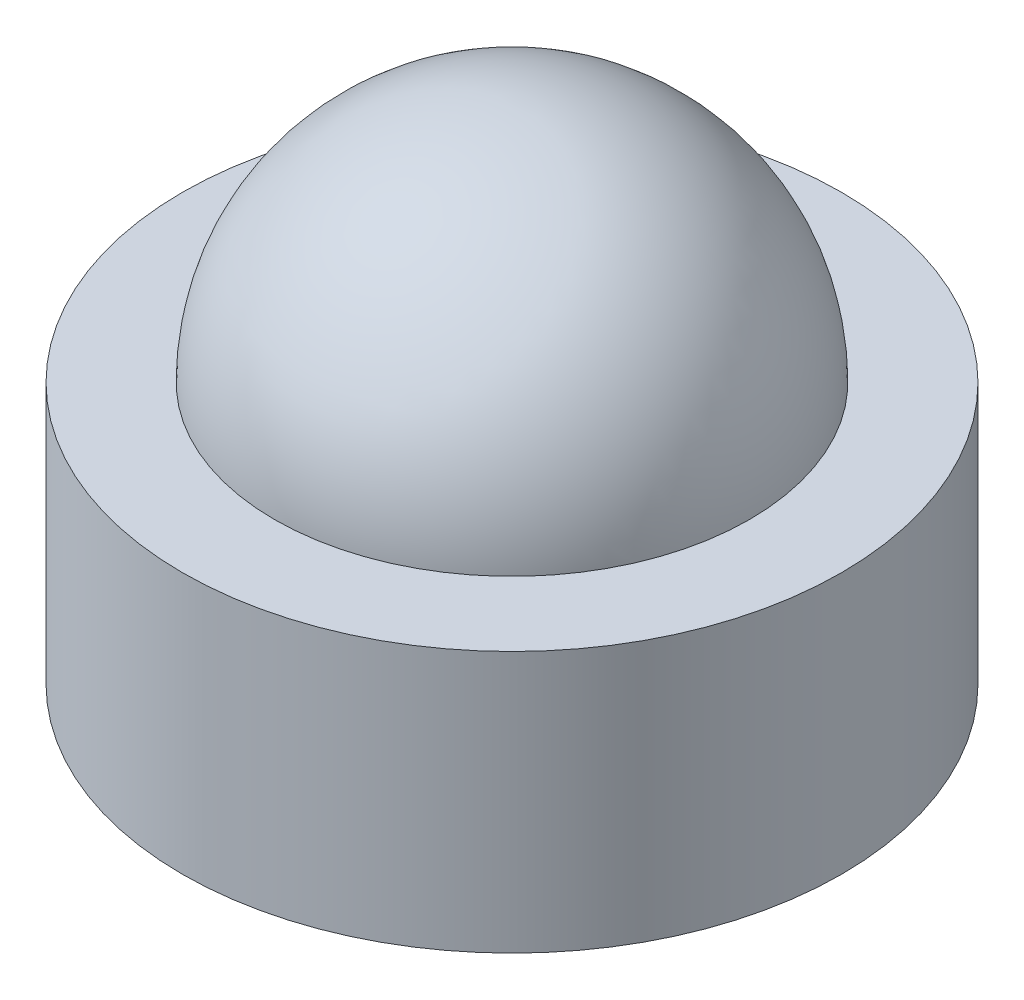
SolidWorks part; units mm, degrees
ref_plane "Front Plane" through (0, 0, 0) normal (0, 0, 1) x (1, 0, 0)
ref_plane "Top Plane" through (0, 0, 0) normal (0, 1, 0) x (1, 0, 0)
ref_plane "Right Plane" through (0, 0, 0) normal (1, 0, 0) x (0, 0, -1)
sketch "Sketch1" plane through (0, 0, 0) normal (0, 1, 0) x (1, 0, 0)
  circle A0 centre (0, 0) radius 55.5
  dimension "D1" = 111
extrude "Boss-Extrude1" add sketch "Sketch1" along normal blind 44
sketch "Sketch3" plane through (0, 0, 0) normal (0, 0, 1) x (1, 0, 0)
  line L0 (0, 44) -> (-40, 44)
  line L1 (55.5, 44) -> (-55.5, 44) construction
  line L2 (0, 44) -> (0, 84)
  arc A0 (0, 84) -> (-40, 44) centre (0, 44) ccw
  dimension "D1" = 40
revolve "Revolve1" add sketch "Sketch3" angle 360 about L2
sketch "Sketch4" plane through (0, 0, 0) normal (0, -1, 0) x (1, 0, 0)
  line L0 (0, 55.5) -> (0, 50.2) construction
  circle A0 centre (0, 50.2) radius 2
  circle A2 centre (0, 0) radius 55.5 construction
  circle A3 centre (43.4745, -25.1) radius 2
  circle A4 centre (-43.4745, -25.1) radius 2
  point P11 (0, 0)
  dimension "D1" = 4
  dimension "D3" = 3
  dimension "D2" = 5.3
extrude "Cut-Extrude1" cut sketch "Sketch4" against normal blind 4
